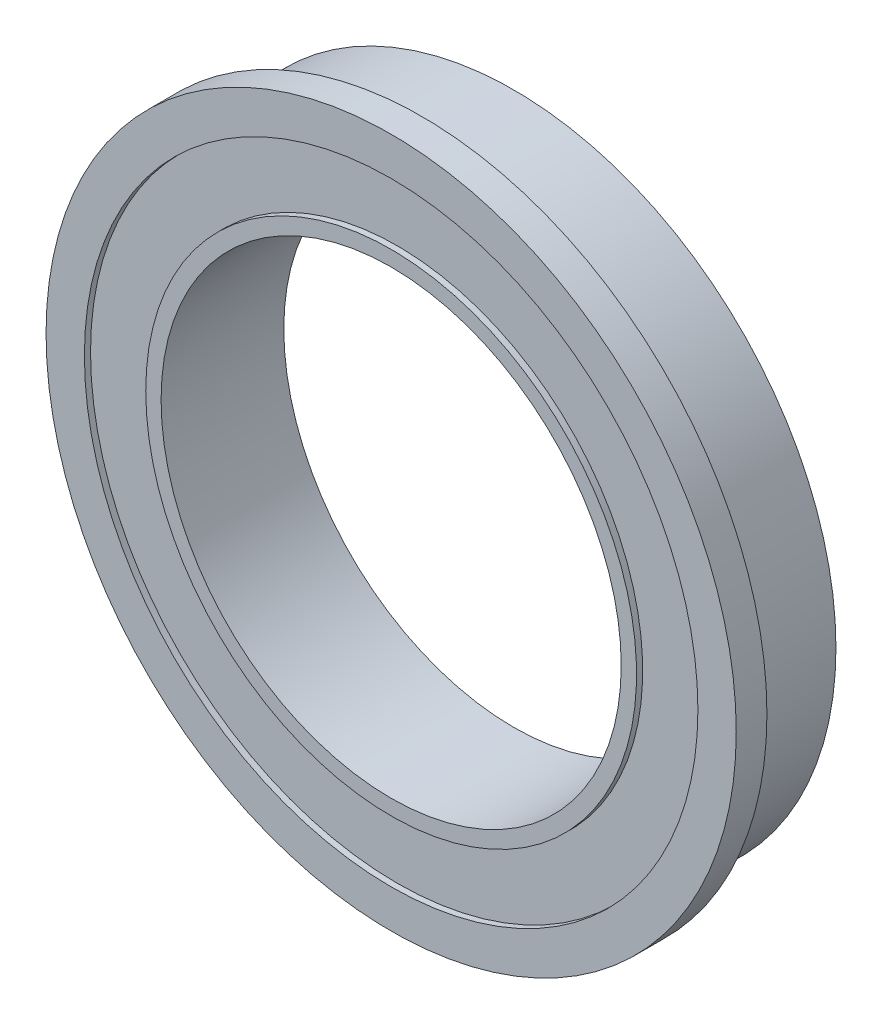
SolidWorks part; units mm, degrees
ref_plane "前视基准面" through (0, 0, 0) normal (0, 0, 1) x (1, 0, 0)
ref_plane "上视基准面" through (0, 0, 0) normal (0, 1, 0) x (1, 0, 0)
ref_plane "右视基准面" through (0, 0, 0) normal (1, 0, 0) x (0, 0, -1)
sketch "草图1" plane through (0, 0, 0) normal (0, 0, 1) x (1, 0, 0)
  circle A0 centre (0, 0) radius 10.5
  circle A1 centre (0, 0) radius 11.25
  dimension "D1" = 21
  dimension "D2" = 22.5
extrude "凸台-拉伸1" add sketch "草图1" along normal blind 1
sketch "草图2" plane through (0, 0, 1) normal (0, 0, 1) x (1, 0, 0)
  circle A0 centre (0, 0) radius 10.5
  circle A1 centre (0, 0) radius 7.5
  circle A3 centre (0, 0) radius 10.5 construction
  dimension "D2" = 15
extrude "凸台-拉伸2" add sketch "草图2" against normal blind 4
sketch "草图3" plane through (0, 0, -3) normal (0, 0, -1) x (-1, 0, 0)
  circle A0 centre (0, 0) radius 8
  circle A1 centre (0, 0) radius 10
  circle A2 centre (0, 0) radius 10.5 construction
  circle A3 centre (0, 0) radius 7.5 construction
  dimension "D1" = 0.5
  dimension "D2" = 0.5
extrude "切除-拉伸1" cut sketch "草图3" against normal blind 0.2
ref_plane "基准面1" through (0, 0, -1) normal (0, 0, -1) x (-1, 0, 0)
mirror "镜向1" about plane through (0, 0, -1) normal (0, 0, -1) of "切除-拉伸1"
